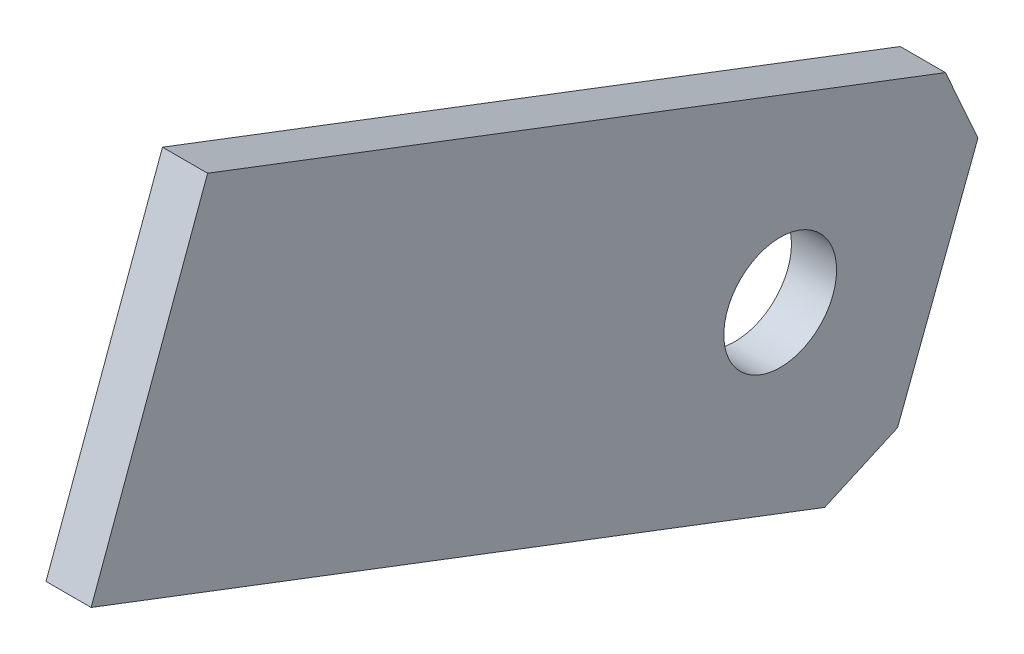
SolidWorks part; units mm, degrees
ref_plane "Front Plane" through (0, 0, 0) normal (0, 0, 1) x (1, 0, 0)
ref_plane "Top Plane" through (0, 0, 0) normal (0, 1, 0) x (1, 0, 0)
ref_plane "Right Plane" through (0, 0, 0) normal (1, 0, 0) x (0, 0, -1)
ref_plane "Plane1" through (0.9, 0, 0) normal (-1, 0, 0) x (0, -1, 0)
sketch "Sketch1" plane through (0.9, 0, 0) normal (-1, 0, 0) x (0, -1, 0)
  line L0 (-360.574, 1589.1666) -> (-332.5476, 1599.8681)
  line L1 (-332.5476, 1599.8681) -> (-359.1572, 1669.5565)
  line L2 (-359.1572, 1669.5565) -> (-387.3277, 1659.2325)
  line L3 (-387.3277, 1659.2325) -> (-360.574, 1589.1666)
  dimension "D1" = 30.0027
  dimension "D2" = 75
extrude "Boss-Extrude1" add sketch "Sketch1" against normal blind 4
hole_wizard "M8 Clearance Hole1" positions "Sketch3" profile "Sketch2" hole size "M8" standard "ANSI Metric"
sketch "Sketch3" plane through (4.9, 0, 0) normal (1, 0, 0) x (0, 0, -1)
  line L0 (-1589.1666, 360.574) -> (-1599.8681, 332.5476) construction
  point P0 (-1608.4831, 352.0357)
  dimension "D1" = 15
sketch "Sketch2" plane through (4.9, 352.0357, 1608.4831) normal (0, 1, 0) x (0, 0, -1)
  line L0 (0, 0) -> (0, 4)
  line L1 (0, 4) -> (4.9995, 4)
  line L2 (4.9995, 4) -> (4.9995, 0)
  line L5 (4.9995, 0) -> (0, 0)
  line L11 (0, -6.35) -> (0, 107.95) construction
  dimension "Thru Hole Dia." = 9.9991
  dimension "Thru Hole Depth" = 4
chamfer "Chamfer1" distance 5 angle 45 2 edges at (2.9, 360.574, 1589.1666) (2.9, 332.5476, 1599.8681)
